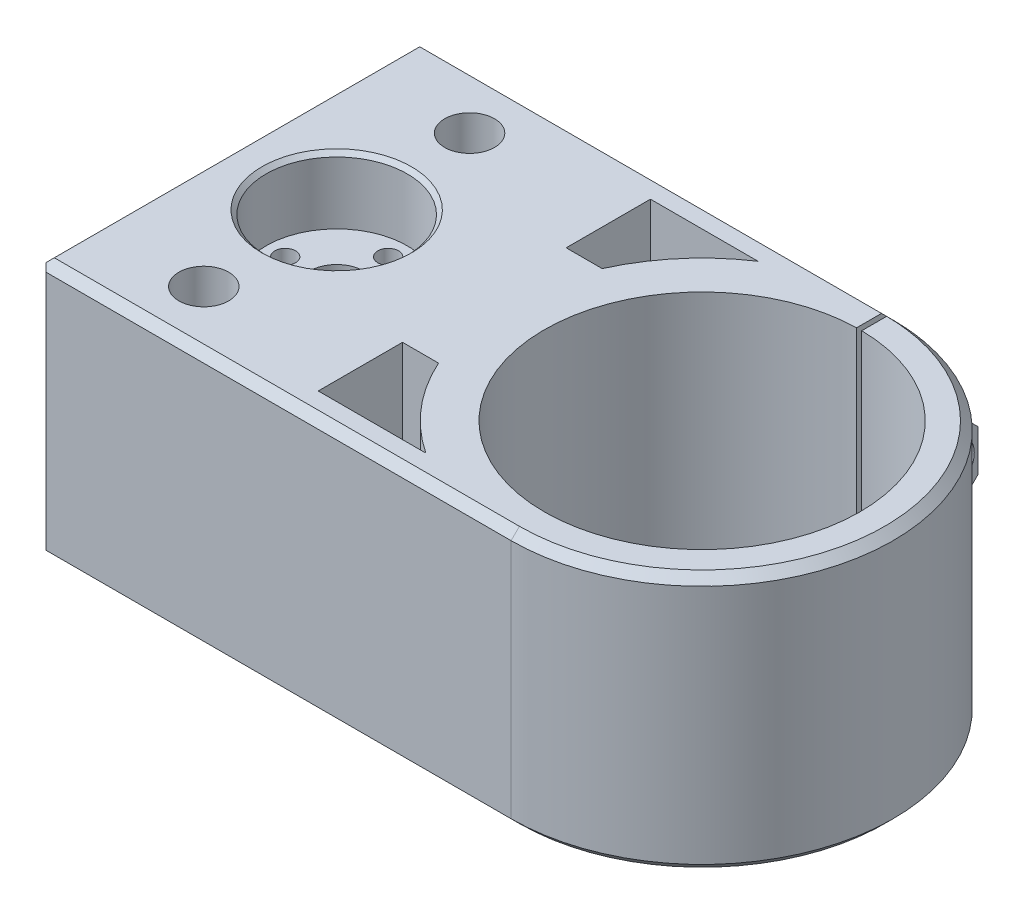
SolidWorks part; units mm, degrees
ref_plane "Front Plane" through (0, 0, 0) normal (0, 0, 1) x (1, 0, 0)
ref_plane "Top Plane" through (0, 0, 0) normal (0, 1, 0) x (1, 0, 0)
ref_plane "Right Plane" through (0, 0, 0) normal (1, 0, 0) x (0, 0, -1)
sketch "Sketch1" plane through (0, 0, 0) normal (0, 1, 0) x (1, 0, 0)
  line L0 (38.4382, 10.9355) -> (38.4382, 20.9368)
  line L1 (-18.7785, 14.9368) -> (33.8215, 14.9368)
  line L2 (-18.7785, 14.9368) -> (-18.7785, -31.0632)
  line L3 (-18.7785, -31.0632) -> (38.2215, -31.0632)
  line L4 (38.4382, 20.9368) -> (42.4382, 20.9368)
  line L5 (42.4382, 20.9368) -> (42.4382, 14.5469)
  line L6 (37.8215, 10.9325) -> (37.8215, 20.9368)
  line L7 (37.8215, 20.9368) -> (33.8215, 20.9368)
  line L8 (33.8215, 20.9368) -> (33.8215, 14.9368)
  line L9 (12, 11.9368) -> (12, 1.7887)
  line L10 (12, 1.7887) -> (16.3369, 1.7887)
  line L11 (12, 11.9368) -> (24.955, 11.9368)
  line L13 (12, -17.9152) -> (16.3369, -17.9152)
  line L14 (12, -28.0632) -> (12, -17.9152)
  line L15 (12, -28.0632) -> (24.955, -28.0632)
  arc A0 (38.2215, -31.0632) -> (42.4382, 14.5469) centre (38.2215, -8.0632) ccw
  arc A1 (37.8215, 10.9325) -> (38.4382, 10.9355) centre (38.2215, -8.0632) ccw
  arc A2 (24.955, 11.9368) -> (16.3369, 1.7887) centre (38.2215, -8.0632) ccw
  arc A3 (24.955, -28.0632) -> (16.3369, -17.9152) centre (38.2215, -8.0632) cw
  dimension "D1" = 38
  dimension "D2" = 6
  dimension "D4" = 0
  dimension "D9" = 23
  dimension "D10" = 24
  dimension "D11" = 24
  dimension "D3" = 6
  dimension "D5" = 12
  dimension "D6" = 3
  dimension "D7" = 46
  dimension "D8" = 3
  dimension "D12" = 57
  dimension "D13" = 4
  dimension "D14" = 4
extrude "Boss-Extrude1" add sketch "Sketch1" along normal blind 31
sketch "Sketch2" plane through (0, 31, 0) normal (0, 1, 0) x (1, 0, 0)
  line L0 (33.8215, 14.9368) -> (38.4382, 14.9368)
  line L1 (42.4382, 14.5469) -> (42.4382, 20.9368) construction
  line L2 (42.4382, 14.9368) -> (42.4382, 20.9368)
  line L3 (42.4382, 20.9368) -> (33.8215, 20.9368)
  line L4 (33.8215, 20.9368) -> (33.8215, 14.9368)
  line L5 (33.8215, 14.9368) -> (33.7741, 14.8632)
  line L6 (42.4382, 14.9368) -> (42.4382, 14.548)
  arc A0 (42.4382, 14.548) -> (38.0049, 14.9368) centre (38.2215, -8.0632) ccw
  line M4 (42.4382, 14.5469) -> (42.4382, 20.9368)
  line M5 (42.4382, 20.9368) -> (38.4382, 20.9368)
  line M6 (38.4382, 20.9368) -> (38.4382, 10.9355)
  line M8 (37.8215, 10.9325) -> (37.8215, 20.9368)
  line M9 (37.8215, 20.9368) -> (33.8215, 20.9368)
  line M10 (33.8215, 20.9368) -> (33.8215, 14.9368)
extrude "Cut-Extrude1" cut sketch "Sketch2" against normal blind 10 contours L0 M6 M4 M5 | L0 M10 M8 M9 | L3 L0 M6 M8
ref_plane "Plane1" through (0, 15.5, 0) normal (0, 1, 0) x (1, 0, 0)
mirror "Mirror1" about plane through (0, 15.5, 0) normal (0, 1, 0) of "Cut-Extrude1"
chamfer "Chamfer1" distance 3 angle 45 4 edges at (40.4382, 10, -20.9368) (35.8215, 10, -20.9368) (40.4382, 21, -20.9368) (35.8215, 21, -20.9368)
sketch "Sketch3" plane through (42.4382, 0, 0) normal (1, 0, 0) x (0, 0, -1)
  line L0 (20.9368, 18) -> (20.9368, 13) construction
  circle A0 centre (17.7368, 15.5) radius 1
  dimension "D1" = 2
  dimension "D3" = 3.2
extrude "Cut-Extrude2" cut sketch "Sketch3" against normal blind 12
sketch "Sketch4" plane through (42.4382, 0, 0) normal (1, 0, 0) x (0, 0, -1)
  circle A0 centre (17.7368, 15.5) radius 2.75
  dimension "D1" = 5.5
extrude "Cut-Extrude3" cut sketch "Sketch4" against normal blind 3
hole_wizard "M3x0.5 Tapped Hole1" positions "3DSketch1" profile "Sketch5" tap size "M3x0.5" standard "ANSI Metric"
sketch3d "3DSketch1"
  line L0 (33.8215, 15.5, -17.7368) -> (37.8215, 15.5, -17.7368) construction
  point P0 (33.8215, 15.5, -17.7368)
sketch "Sketch5" plane through (33.8215, 15.5, -17.7368) normal (0, 1, 0) x (0, 0, 1)
  line L0 (0, 0) -> (0, 6.2511)
  line L1 (0, 6.2511) -> (1.25, 5.5)
  line L2 (1.25, 5.5) -> (1.25, 0)
  line L5 (1.25, 0) -> (0, 0)
  line L10 (0, 6.2511) -> (-1.25, 5.5) construction
  line L11 (0, -6.35) -> (0, 107.95) construction
  dimension "Tap Drill Dia." = 2.5
  dimension "Tap Drill Depth" = 5.5
  dimension "Drill Angle" = 118
cosmetic thread "Hole Thread1" parameters "D1"=4, "D2"=3
chamfer "Chamfer2" distance 1 angle 45 4 edges at (9.5215, 31, -14.9368) (-18.7785, 31, 8.0632) (9.7215, 31, 31.0632) (61.1239, 31, 10.1806)
chamfer "Chamfer3" distance 1 angle 45 1 edges at (40.4467, 31, -14.8299)
chamfer "Chamfer4" distance 1 angle 45 4 edges at (61.1239, 0, 10.1806) (9.7215, 0, 31.0632) (-18.7785, 0, 8.0632) (9.5215, 0, -14.9368)
chamfer "Chamfer5" distance 1 angle 45 1 edges at (40.4467, 0, -14.8299)
chamfer "Chamfer6" distance 1 angle 45 2 edges at (-18.7785, 15.5, 31.0632) (-18.7785, 15.5, -14.9368)
sketch "Sketch6" plane through (0, 31, 0) normal (0, 1, 0) x (1, 0, 0)
  line L0 (-18.7785, -30.0632) -> (-18.7785, 13.9368) construction
  line L1 (-17.7785, 14.9368) -> (37.8215, 14.9368) construction
  line L2 (38.2215, -31.0632) -> (-17.7785, -31.0632) construction
  circle A0 centre (-5.7785, -24.0632) radius 3
  circle A1 centre (-5.7785, 7.9368) radius 3
  dimension "D1" = 13
  dimension "D2" = 7
  dimension "D3" = 7
  dimension "D4" = 13
  dimension "D5" = 6
  dimension "D6" = 6
extrude "Cut-Extrude4" cut sketch "Sketch6" against normal through all
sketch "Sketch7" plane through (0, 31, 0) normal (0, 1, 0) x (1, 0, 0)
  line L0 (-18.7785, -30.0632) -> (-18.7785, 13.9368) construction
  line L1 (-17.7785, 14.9368) -> (37.8215, 14.9368) construction
  circle A0 centre (-5.7785, -8.0632) radius 8.5
  dimension "D1" = 13
  dimension "D2" = 17
  dimension "D3" = 23
extrude "Cut-Extrude5" cut sketch "Sketch7" against normal blind 8
chamfer "Chamfer7" distance 0.5 angle 45 1 edges at (-5.7785, 31, 16.5632)
ref_plane "Plane2" through (0, 15.5, 0) normal (0, 1, 0) x (1, 0, 0)
mirror "Mirror3" about plane through (0, 15.5, 0) normal (0, 1, 0) of "Cut-Extrude5"
chamfer "Chamfer8" distance 0.5 angle 45 1 edges at (-5.7785, 0, 16.5632)
sketch "Sketch8" plane through (0, 23, 0) normal (0, 1, 0) x (1, 0, 0)
  circle A0 centre (-5.7785, -8.0632) radius 3.25
  dimension "D1" = 6.5
extrude "Cut-Extrude6" cut sketch "Sketch8" against normal through all
sketch "Sketch9" plane through (0, 23, 0) normal (0, 1, 0) x (1, 0, 0)
  circle A0 centre (-5.7785, -1.8632) radius 1
  circle A1 centre (-5.7785, -8.0632) radius 3.25 construction
  dimension "D2" = 0
  dimension "D3" = 2
  dimension "D1" = 6.2
extrude "Cut-Extrude7" cut sketch "Sketch9" against normal blind 26
hole_wizard "M3x0.5 Tapped Hole2" positions "3DSketch3" profile "Sketch10" tap size "M3x0.5" standard "ANSI Metric"
sketch3d "3DSketch3"
  line L0 (-5.7785, 8, 1.8632) -> (-5.7785, 23, 1.8632) construction
  point P0 (-5.7785, 23, 1.8632)
sketch "Sketch10" plane through (-5.7785, 23, 1.8632) normal (1, 0, 0) x (0, 0, 1)
  line L0 (0, 0) -> (0, 27.2511)
  line L1 (0, 27.2511) -> (1.25, 26.5)
  line L2 (1.25, 26.5) -> (1.25, 0)
  line L5 (1.25, 0) -> (0, 0)
  line L10 (0, 27.2511) -> (-1.25, 26.5) construction
  line L11 (0, -6.35) -> (0, 107.95) construction
  dimension "Tap Drill Dia." = 2.5
  dimension "Tap Drill Depth" = 26.5
  dimension "Drill Angle" = 118
cosmetic thread "Hole Thread2" parameters "D1"=15, "D2"=3
pattern_circular "CirPattern1" count 4 every 90 about axis through (-5.7785, 0, 8.0632) along (0, 1, 0) of "Cut-Extrude7", "M3x0.5 Tapped Hole2"
